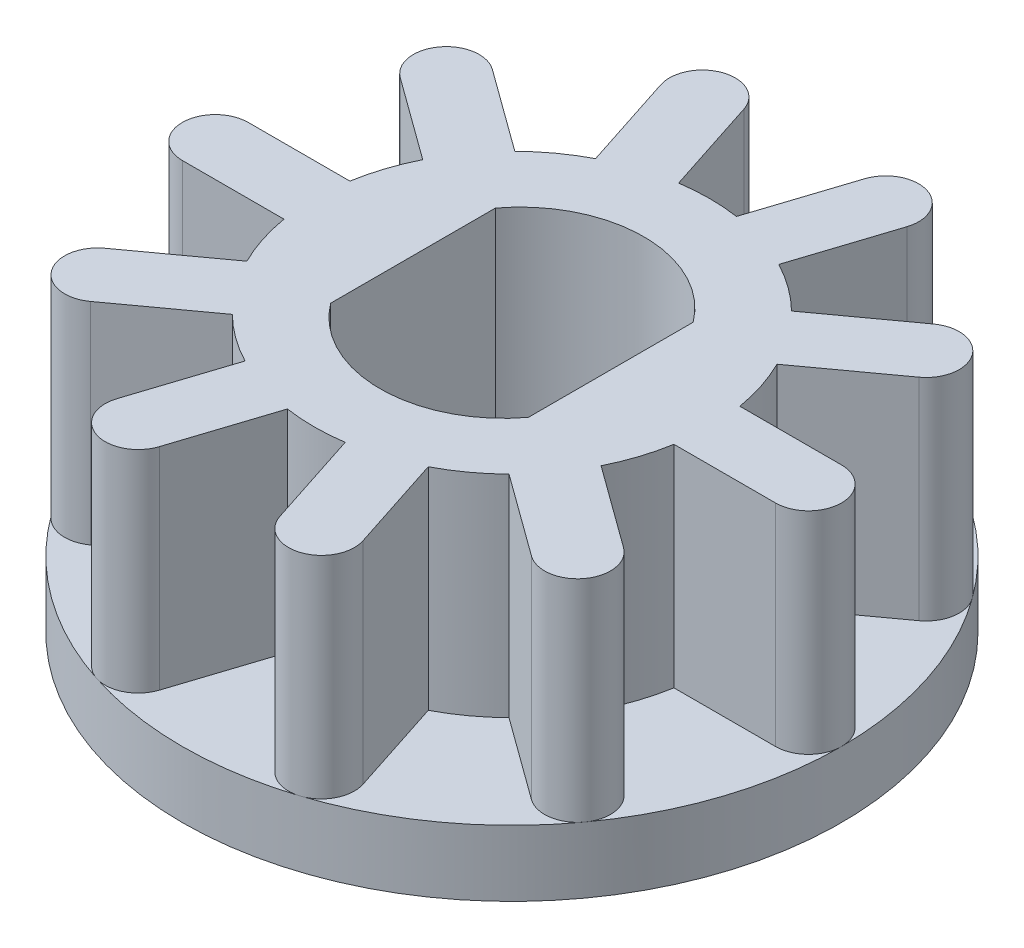
SolidWorks part; units mm, degrees
ref_plane "Front Plane" through (0, 0, 0) normal (0, 0, 1) x (1, 0, 0)
ref_plane "Top Plane" through (0, 0, 0) normal (0, 1, 0) x (1, 0, 0)
ref_plane "Right Plane" through (0, 0, 0) normal (1, 0, 0) x (0, 0, -1)
sketch "Sketch1" plane through (0, 0, 0) normal (0, 1, 0) x (1, 0, 0)
  circle A0 centre (0, 0) radius 5
extrude "Boss-Extrude1" add sketch "Sketch1" along normal blind 4.2 contours A0
sketch "Sketch2" plane through (0, 4.2, 0) normal (0, 1, 0) x (1, 0, 0)
  line L5 (-1.5, 1.25) -> (-1.5, -1.25)
  line L6 (1.5, -1.25) -> (1.5, 1.25)
  arc A1 (-1.5, 1.25) -> (1.5, 1.25) centre (0, 0.125) cw
  arc A2 (-1.5, -1.25) -> (1.5, -1.25) centre (0, -0.125) ccw
extrude "Cut-Extrude2" cut sketch "Sketch2" against normal through all contours L6 A1 L5 A2
sketch "Sketch6" plane through (0, 4.2, 0) normal (0, 1, 0) x (1, 0, 0)
  circle A0 centre (0, 0) radius 3
  circle A1 centre (0, 0) radius 5
extrude "Cut-Extrude4" cut sketch "Sketch6" against normal blind 3.2
sketch "Sketch7" plane through (0, 1, 0) normal (0, 1, 0) x (1, 0, 0)
  line L0 (3.9345, -2.2405) -> (2.687, -1.3342)
  line L1 (4.5, 0.5) -> (2.958, 0.5)
  line L2 (4.5, -0.5) -> (2.958, -0.5)
  line L3 (3.3467, -3.0495) -> (2.0992, -2.1432)
  line L4 (1.8661, -4.1252) -> (1.3896, -2.6588)
  line L5 (0.915, -4.4343) -> (0.4386, -2.9678)
  line L6 (-0.915, -4.4343) -> (-0.4386, -2.9678)
  line L7 (-1.8661, -4.1252) -> (-1.3896, -2.6588)
  line L8 (-3.3467, -3.0495) -> (-2.0992, -2.1432)
  line L9 (-3.9345, -2.2405) -> (-2.687, -1.3342)
  line L10 (-4.5, -0.5) -> (-2.958, -0.5)
  line L11 (-4.5, 0.5) -> (-2.958, 0.5)
  line L12 (-3.9345, 2.2405) -> (-2.687, 1.3342)
  line L13 (-3.3467, 3.0495) -> (-2.0992, 2.1432)
  line L14 (-1.8661, 4.1252) -> (-1.3896, 2.6588)
  line L15 (-0.915, 4.4343) -> (-0.4386, 2.9678)
  line L16 (0.915, 4.4343) -> (0.4386, 2.9678)
  line L17 (1.8661, 4.1252) -> (1.3896, 2.6588)
  line L18 (3.3467, 3.0495) -> (2.0992, 2.1432)
  line L19 (3.9345, 2.2405) -> (2.687, 1.3342)
  circle A5 centre (0, 0) radius 3 construction
  circle A7 centre (0, 0) radius 5 construction
  arc A8 (4.5, -0.5) -> (4.5, 0.5) centre (4.5, 0) ccw
  arc A9 (3.3467, -3.0495) -> (3.9345, -2.2405) centre (3.6406, -2.645) ccw
  arc A10 (0.915, -4.4343) -> (1.8661, -4.1252) centre (1.3906, -4.2798) ccw
  arc A11 (-1.8661, -4.1252) -> (-0.915, -4.4343) centre (-1.3906, -4.2798) ccw
  arc A12 (-3.9345, -2.2405) -> (-3.3467, -3.0495) centre (-3.6406, -2.645) ccw
  arc A13 (-4.5, 0.5) -> (-4.5, -0.5) centre (-4.5, 0) ccw
  arc A14 (-3.3467, 3.0495) -> (-3.9345, 2.2405) centre (-3.6406, 2.645) ccw
  arc A15 (-0.915, 4.4343) -> (-1.8661, 4.1252) centre (-1.3906, 4.2798) ccw
  arc A16 (1.8661, 4.1252) -> (0.915, 4.4343) centre (1.3906, 4.2798) ccw
  arc A17 (3.9345, 2.2405) -> (3.3467, 3.0495) centre (3.6406, 2.645) ccw
  circle A18 centre (0, 0) radius 3
  point P58 (0, 0)
  circle M4 centre (0, 0) radius 3
  dimension "D1" = 10
extrude "Boss-Extrude3" add sketch "Sketch7" along normal blind 3.2 contours L13 A14 L12 M4 | L15 A15 L14 M4 | L17 A16 L16 M4 | L19 A17 L18 M4 | L2 A8 L1 M4 | A9 L0 L3 M4 | A10 L4 L5 M4 | L7 A11 L6 M4 | L9 A12 L8 M4 | L11 A13 L10 M4
